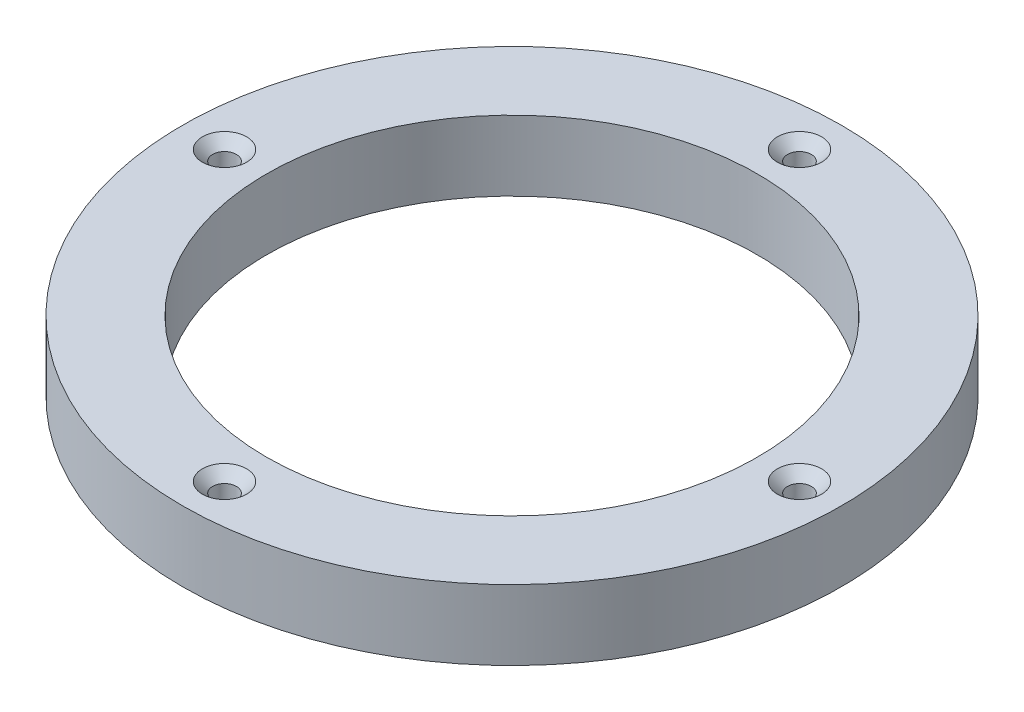
SolidWorks part; units mm, degrees
ref_plane "Piano frontale" through (0, 0, 0) normal (0, 0, 1) x (1, 0, 0)
ref_plane "Piano superiore" through (0, 0, 0) normal (0, 1, 0) x (1, 0, 0)
ref_plane "Piano destro" through (0, 0, 0) normal (1, 0, 0) x (0, 0, -1)
sketch "Schizzo1" plane through (0, 0, 0) normal (0, 1, 0) x (1, 0, 0)
  circle A0 centre (0, 0) radius 35
  circle A1 centre (0, 0) radius 47
  dimension "D1" = 70
  dimension "D2" = 12
extrude "Estrusione-Estrusione1" add sketch "Schizzo1" along normal blind 10
hole_wizard "Foro svasato per Vite M3-1" positions "Schizzo3D1" profile "Schizzo3" countersink size "M3" standard "ISO"
sketch3d "Schizzo3D1"
  line L0 (-41, 10, 0) -> (41, 10, 0) construction
  line L2 (0, 10, -41) -> (0, 10, 41) construction
  line L3 (0, 0, 0) -> (0, 10, 0) construction
  line L4 (0, 10, 0) -> (0, 0, 0) construction
  circle A1 centre (0, 10, 0) radius 47 construction
  point P0 (-41, 10, 0)
  point P2 (41, 10, 0)
  point P4 (0, 10, 41)
  point P6 (0, 10, -41)
  point P32 (0, 57, 0)
  dimension "D1" = 41
  dimension "D2" = 41
  dimension "D3" = 41
  dimension "D4" = 41
sketch "Schizzo3" plane through (-41, 10, 0) normal (1, 0, 0) x (0, 0, 1)
  line L0 (0, 0) -> (0, 189.0215)
  line L1 (0, 189.0215) -> (1.7, 188)
  line L2 (1.7, 188) -> (1.7, 1.45)
  line L3 (1.7, 1.45) -> (3.15, 0)
  line L5 (3.15, 0) -> (0, 0)
  line L6 (-1.7, 1.45) -> (-3.15, 0) construction
  line L10 (0, 189.0215) -> (-1.7, 188) construction
  line L11 (0, -6.35) -> (0, 107.95) construction
  dimension "Hole Dia." = 3.4
  dimension "Hole Depth" = 188
  dimension "Near C'Sink Dia." = 6.3
  dimension "Near C'Sink Angle" = 90
  dimension "Drill Angle" = 118
sketch "Schizzo4" plane through (0, 10, 0) normal (0, 1, 0) x (1, 0, 0)
  point P0 (0, -41)
  point P1 (-41, 0)
  point P3 (0, 41)
  point P5 (41, 0)
